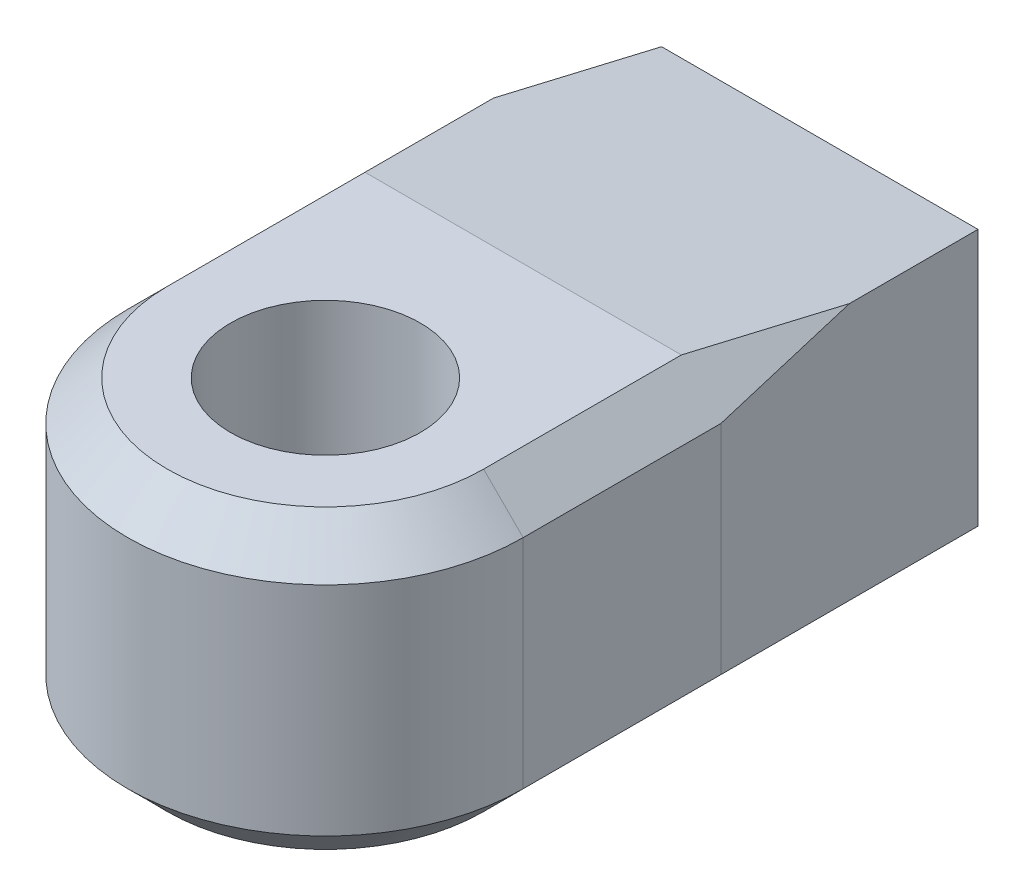
SolidWorks part; units mm, degrees
ref_plane "Front Plane" through (0, 0, 0) normal (0, 0, 1) x (1, 0, 0)
ref_plane "Top Plane" through (0, 0, 0) normal (0, 1, 0) x (1, 0, 0)
ref_plane "Right Plane" through (0, 0, 0) normal (1, 0, 0) x (0, 0, -1)
sketch "Sketch1" plane through (0, 0, 0) normal (0, 1, 0) x (1, 0, 0)
  line L1 (-10, 0) -> (10, 0)
  line L2 (-10, 0) -> (-10, 25)
  line L3 (-10, 25) -> (10, 25)
  line L4 (10, 0) -> (10, 25)
  circle A0 centre (0, 0) radius 4.8
  circle A1 centre (0, 0) radius 10
  dimension "D1" = 9.6
  dimension "D2" = 20
  dimension "D3" = 25
extrude "Boss-Extrude1" add sketch "Sketch1" along normal blind 15 contours A1 L4 L3 L2 | L1 A1 A0 | L1 A1 A0
chamfer "Chamfer1" distance 15 distance2 2 3 edges at (10, 7.5, -25) (-10, 7.5, -25) (0, 15, -25)
sketch "Sketch2" plane through (0, 0, -25) normal (0, 0, -1) x (-1, 0, 0)
  line L0 (8, 0) -> (-8, 0) construction
  line L1 (10, 15) -> (10, 0) construction
  circle A0 centre (0, 7.2) radius 3
  dimension "D1" = 6
  dimension "D2" = 7.2
  dimension "D3" = 10
extrude "Cut-Extrude1" cut sketch "Sketch2" against normal blind 15
chamfer "Chamfer2" distance 2 angle 45 6 edges at (0, 0, 10) (0, 15, 10) (-10, 15, -5) (-10, 0, -5) (10, 0, -5) (10, 15, -5)
